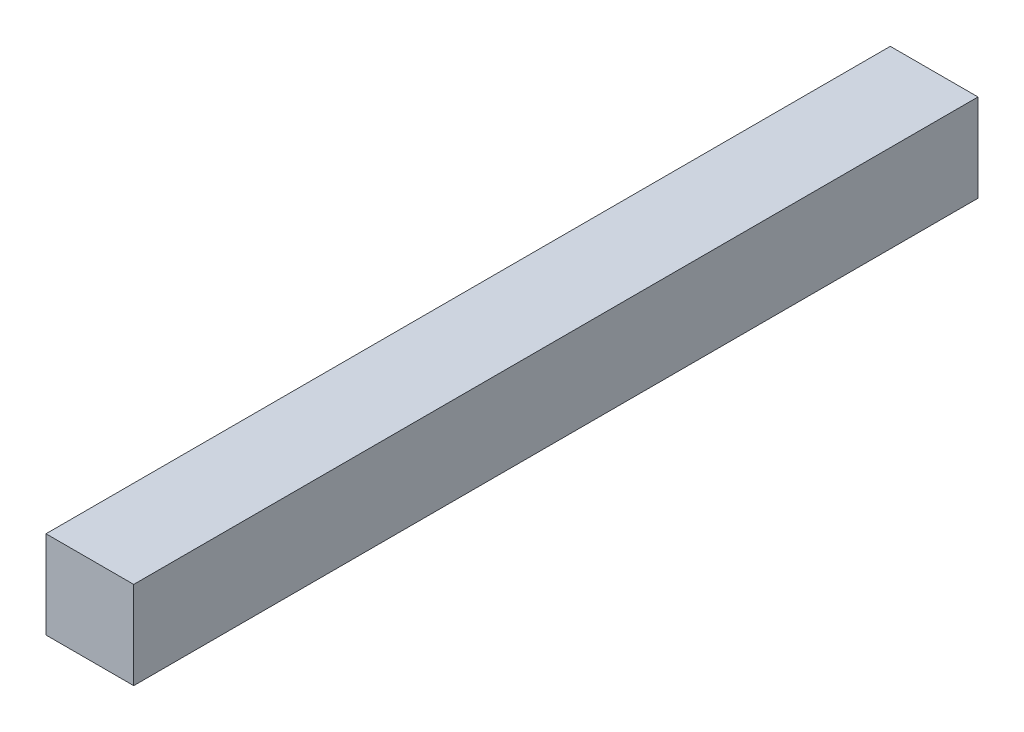
SolidWorks part; units mm, degrees
ref_plane "Front Plane" through (0, 0, 0) normal (0, 0, 1) x (1, 0, 0)
ref_plane "Top Plane" through (0, 0, 0) normal (0, 1, 0) x (1, 0, 0)
ref_plane "Right Plane" through (0, 0, 0) normal (1, 0, 0) x (0, 0, -1)
sketch "Sketch1" plane through (0, 0, 0) normal (0, 0, 1) x (1, 0, 0)
  line L1 (-4, -4) -> (4, -4)
  line L2 (-4, -4) -> (-4, 4)
  line L3 (-4, 4) -> (4, 4)
  line L4 (4, -4) -> (4, 4)
  line L5 (-4, -4) -> (4, 4) construction
  line L6 (-4, 4) -> (4, -4) construction
  point P0 (0, 0)
  dimension "D1" = 8
extrude "Boss-Extrude1" add sketch "Sketch1" along normal mid plane 77
